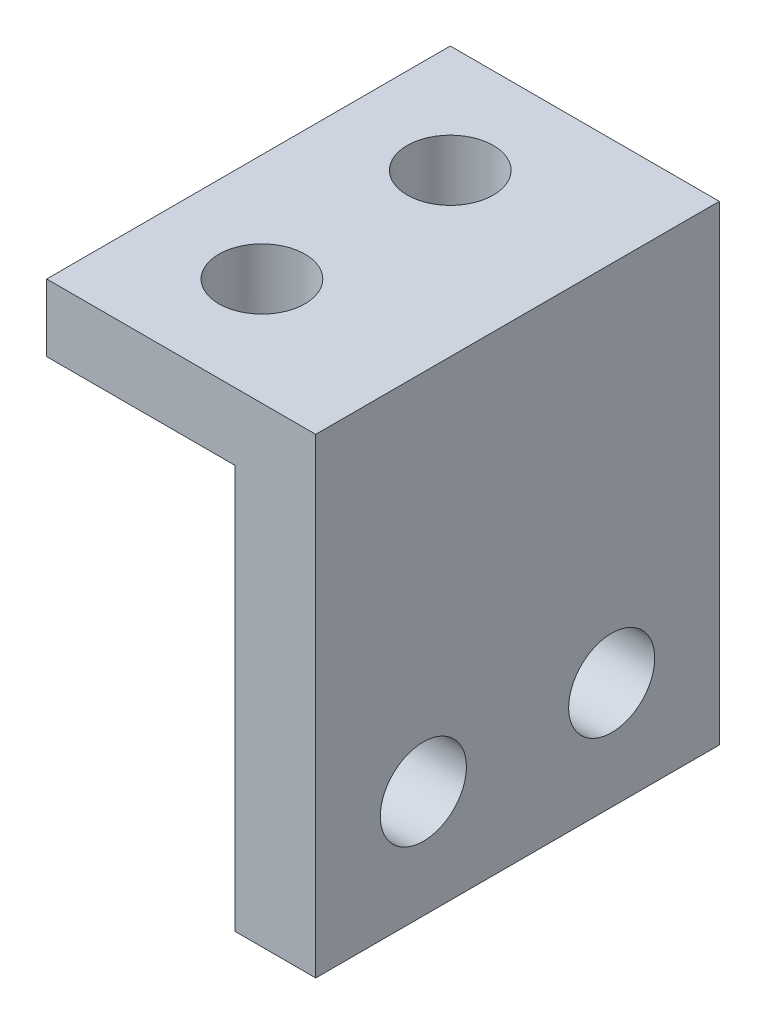
SolidWorks part; units mm, degrees
ref_plane "Front Plane" through (0, 0, 0) normal (0, 0, 1) x (1, 0, 0)
ref_plane "Top Plane" through (0, 0, 0) normal (0, 1, 0) x (1, 0, 0)
ref_plane "Right Plane" through (0, 0, 0) normal (1, 0, 0) x (0, 0, -1)
sketch "Sketch1" plane through (0, 0, 0) normal (0, 0, 1) x (1, 0, 0)
  line L0 (0, 0) -> (-7, 0)
  line L1 (-7, 0) -> (-7, 2.5)
  line L2 (-7, 2.5) -> (3, 2.5)
  line L3 (3, 2.5) -> (3, -15)
  line L4 (3, -15) -> (0, -15)
  line L5 (0, -15) -> (0, 0)
  dimension "D1" = 7
  dimension "D2" = 15
  dimension "D3" = 2.5
  dimension "D4" = 3
extrude "Boss-Extrude1" add sketch "Sketch1" along normal mid plane 15
sketch "Sketch2" plane through (0, 2.5, 0) normal (0, 1, 0) x (1, 0, 0)
  line L0 (-7, -7.5) -> (-7, 7.5) construction
  line L1 (3, 7.5) -> (-7, 7.5) construction
  line L2 (3, -7.5) -> (-7, -7.5) construction
  circle A0 centre (-3, 3.5) radius 1.6
  circle A1 centre (-3, -3.5) radius 1.6
  dimension "D3" = 3.2
  dimension "D4" = 3.2
  dimension "D1" = 4
  dimension "D2" = 4
  dimension "D5" = 4
  dimension "D6" = 4
extrude "Cut-Extrude1" cut sketch "Sketch2" against normal blind 15
sketch "Sketch3" plane through (3, 0, 0) normal (1, 0, 0) x (0, 0, -1)
  line L0 (-7.5, -15) -> (7.5, -15) construction
  line L1 (7.5, -15) -> (7.5, 2.5) construction
  line L2 (-7.5, -15) -> (-7.5, 2.5) construction
  circle A0 centre (3.5, -11) radius 1.6
  circle A1 centre (-3.5, -11) radius 1.6
  dimension "D1" = 3.2
  dimension "D2" = 3.2
  dimension "D3" = 4
  dimension "D4" = 4
  dimension "D5" = 4
  dimension "D6" = 4
extrude "Cut-Extrude2" cut sketch "Sketch3" against normal blind 15
sketch "Sketch4" plane through (0, -15, 0) normal (0, -1, 0) x (1, 0, 0)
  circle A0 centre (-1.7, 3.5) radius 2.5
  circle A1 centre (-1.7, -3.5) radius 2.5
  point P2 (-3, -3.5)
  point P4 (0, 0)
  point P6 (0, 0)
  dimension "D2" = 5
  dimension "D3" = 5
  dimension "D1" = 1.3
extrude "Cut-Extrude3" cut sketch "Sketch4" against normal up to surface (15 mm away) up to face at (-4.6, 0, -3.5)
